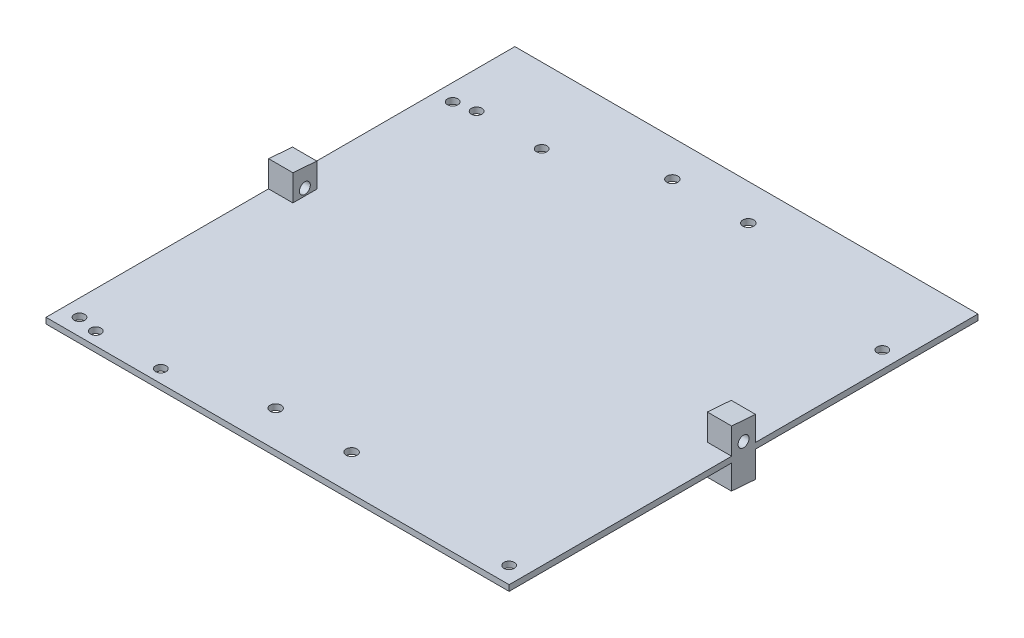
SolidWorks part; units mm, degrees
material "Thornel Mat VMA"
ref_plane "Front Plane" through (0, 0, 0) normal (0, 0, 1) x (1, 0, 0)
ref_plane "Top Plane" through (0, 0, 0) normal (0, 1, 0) x (1, 0, 0)
ref_plane "Right Plane" through (0, 0, 0) normal (1, 0, 0) x (0, 0, -1)
sketch "Sketch1" plane through (0, 0, 0) normal (0, 1, 0) x (1, 0, 0)
  line L1 (0, 0) -> (96.8, 0)
  line L2 (0, 0) -> (0, -98)
  line L3 (0, -98) -> (96.8, -98)
  line L4 (96.8, 0) -> (96.8, -98)
  dimension "D1" = 98
  dimension "D2" = 96.8
extrude "Boss-Extrude1" add sketch "Sketch1" along normal blind 1.2192
sketch "Sketch5" plane through (0, 0, 0) normal (0, -1, 0) x (-1, 0, 0)
  line L1 (0, -98) -> (-96.8, -98) construction
  line L2 (0, 0) -> (0, -98) construction
  line L3 (-96.8, 0) -> (0, 0) construction
  circle A0 centre (-3.5, -94.5) radius 1.0922
  circle A1 centre (-7.7, -95.3) radius 1.0922
  circle A2 centre (-21.3, -95.3) radius 1.0922
  circle A3 centre (-93.3, -94.5) radius 1.0922
  circle A4 centre (-93.3, -16.5) radius 1.0922
  circle A5 centre (-3.5, -16.5) radius 1.0922
  circle A6 centre (-7.7, -15.7) radius 1.0922
  circle A7 centre (-21.3, -15.7) radius 1.0922
  dimension "D1" = 3.5
  dimension "D2" = 93.3
  dimension "D3" = 72
  dimension "D5" = 85.6
  dimension "D6" = 2.7
  dimension "D7" = 89.8
  dimension "D8" = 3.5
  dimension "D9" = 16.5
  dimension "D10" = 93.3
  dimension "D11" = 72
  dimension "D12" = 2.1844
  dimension "D13" = 15.7
  dimension "D15" = 15.7
  dimension "D16" = 16.5
  dimension "D17" = 89.8
  dimension "D4" = 2.7
  dimension "D14" = 85.6
extrude "Cut-Extrude1" cut sketch "Sketch5" against normal up to next
sketch "Sketch6" plane through (0, 1.2192, 0) normal (0, 1, 0) x (1, 0, 0)
  line L0 (96.8, 0) -> (0, 0) construction
  line L1 (56.3375, -7.5406) -> (40.4625, -7.5406) construction
  line L3 (96.8, -49) -> (0, -49) construction
  line L4 (96.8, -98) -> (96.8, 0) construction
  line L5 (0, 0) -> (0, -98) construction
  circle A0 centre (56.3375, -7.5406) radius 1.143
  circle A1 centre (40.4625, -7.5406) radius 1.143
  circle A2 centre (40.4625, -90.4594) radius 1.143
  circle A3 centre (56.3375, -90.4594) radius 1.143
  dimension "D1" = 2.286
  dimension "D2" = 2.286
  dimension "D6" = 40.4625
  dimension "D3" = 7.5406
  dimension "D4" = 7.5406
  dimension "D5" = 15.875
extrude "Cut-Extrude2" cut sketch "Sketch6" against normal up to next
sketch "Sketch10" plane through (96.8, 0, 0) normal (1, 0, 0) x (0, 0, -1)
  line L0 (-98, 1.2192) -> (0, 1.2192) construction
  line L1 (-46.5, 1.2192) -> (-51.5, 1.2192)
  line L2 (-46.5, 1.2192) -> (-46.5, 6.2992)
  line L3 (-46.5, 6.2992) -> (-51.5, 6.2992)
  line L4 (-51.5, 1.2192) -> (-51.5, 6.2992)
  line L5 (-98, 0.6096) -> (0, 0.6096) construction
  line L6 (-98, 1.2192) -> (-98, 0) construction
  line L7 (0, 1.2192) -> (0, 0) construction
  circle A0 centre (-49, 2.648) radius 1.143
  point P6 (-49, 1.2192)
  point P7 (-49, 1.2192)
  point P9 (-49, 6.2992)
  dimension "D3" = 2.286
  dimension "D4" = 2.0383
  dimension "D1" = 5.08
  dimension "D2" = 5
extrude "Boss-Extrude2" add sketch "Sketch10" against normal blind 96.774
sketch "Sketch12" plane through (0, 1.2192, 0) normal (0, 1, 0) x (1, 0, 0)
  line L0 (48.4, -98) -> (48.4, 0) construction
  line L1 (0, -98) -> (96.8, -98) construction
  line L2 (96.8, 0) -> (0, 0) construction
sketch "Sketch13" plane through (0, 6.2992, 0) normal (0, 1, 0) x (1, 0, 0)
  line L0 (0.026, -51.5) -> (96.8, -51.5) construction
  line L1 (91.72, -51.5) -> (5.106, -51.5)
  line L2 (91.72, -51.5) -> (91.72, -46.5)
  line L3 (91.72, -46.5) -> (5.106, -46.5)
  line L4 (5.106, -51.5) -> (5.106, -46.5)
  line L5 (0.026, -46.5) -> (96.8, -46.5) construction
  line L6 (96.8, -46.5) -> (96.8, -51.5) construction
  line L7 (0.026, -46.5) -> (0.026, -51.5) construction
  dimension "D1" = 5.08
  dimension "D2" = 5.08
extrude "Cut-Extrude3" cut sketch "Sketch13" against normal blind 5.08
sketch "Sketch14" plane through (0, 0, 0) normal (0, -1, 0) x (1, 0, 0)
  line L0 (0, 49) -> (0, 51.54)
  line L1 (0, 0) -> (0, 98) construction
  line L2 (0, 51.54) -> (5.08, 51.54)
  line L3 (5.08, 51.54) -> (5.08, 46.46)
  line L4 (5.08, 46.46) -> (0, 46.46)
  line L5 (0, 46.46) -> (0, 49)
  line L6 (96.8, 49) -> (96.8, 51.54)
  line L7 (96.8, 98) -> (96.8, 0) construction
  line L8 (96.8, 51.54) -> (91.72, 51.54)
  line L9 (91.72, 51.54) -> (91.72, 46.46)
  line L10 (91.72, 46.46) -> (96.8, 46.46)
  line L11 (96.8, 46.46) -> (96.8, 49)
  dimension "D1" = 2.54
  dimension "D2" = 5.08
  dimension "D3" = 2.54
  dimension "D4" = 5.08
  dimension "D5" = 5.08
  dimension "D6" = 2.54
  dimension "D7" = 2.54
extrude "Boss-Extrude3" add sketch "Sketch14" along normal blind 5.08
sketch "Sketch15" plane through (0, 0, 0) normal (-1, 0, 0) x (0, 0, 1)
  line L0 (51.54, -5.08) -> (46.46, -5.08)
  line L1 (46.46, -5.08) -> (46.46, -5.4798)
  line L2 (46.46, -5.4798) -> (51.54, -5.08)
  dimension "D1" = 4.5
extrude "Boss-Extrude5" add sketch "Sketch15" against normal blind 5.08
sketch "Sketch16" plane through (96.8, 0, 0) normal (1, 0, 0) x (0, 0, -1)
  line L0 (-46.46, -5.08) -> (-51.54, -5.08)
  line L1 (-46.46, -5.08) -> (-46.46, -5.4798)
  line L2 (-46.46, -5.4798) -> (-51.54, -5.08)
  dimension "D1" = 4.5
extrude "Boss-Extrude6" add sketch "Sketch16" against normal blind 5.08
sketch "Sketch17" plane through (96.8, 0, 0) normal (1, 0, 0) x (0, 0, -1)
  line L0 (-46.5, 6.2992) -> (-51.5, 6.2992)
  line L1 (-51.5, 6.2992) -> (-51.5, 6.6927)
  line L2 (-51.5, 6.6927) -> (-46.5, 6.2992)
  dimension "D1" = 4.5
extrude "Boss-Extrude7" add sketch "Sketch17" against normal blind 5.08
sketch "Sketch18" plane through (0.026, 0, 0) normal (-1, 0, 0) x (0, 0, 1)
  line L0 (46.5, 6.2992) -> (51.5, 6.2992)
  line L1 (51.5, 6.2992) -> (51.5, 6.6927)
  line L2 (51.5, 6.6927) -> (46.5, 6.2992)
  dimension "D1" = 4.5
extrude "Boss-Extrude8" add sketch "Sketch18" against normal blind 5.08
